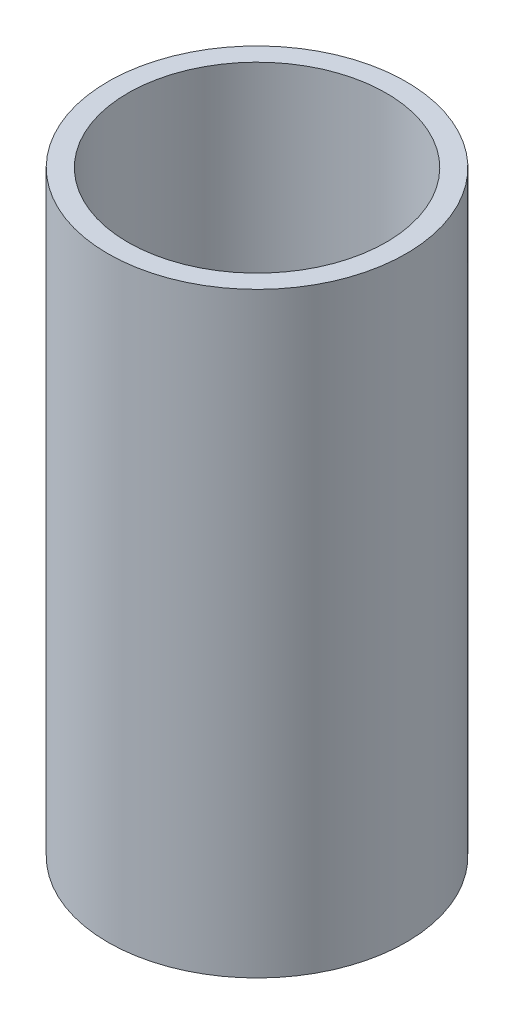
SolidWorks part; units mm, degrees
ref_plane "Front Plane" through (0, 0, 0) normal (0, 0, 1) x (1, 0, 0)
ref_plane "Top Plane" through (0, 0, 0) normal (0, 1, 0) x (1, 0, 0)
ref_plane "Right Plane" through (0, 0, 0) normal (1, 0, 0) x (0, 0, -1)
sketch "Sketch1" plane through (0, 0, 0) normal (0, 1, 0) x (1, 0, 0)
  circle A0 centre (0, 0) radius 26
  circle A1 centre (0, 0) radius 30
  dimension "D1" = 52
  dimension "D2" = 60
extrude "Boss-Extrude1" add sketch "Sketch1" along normal mid plane 120
